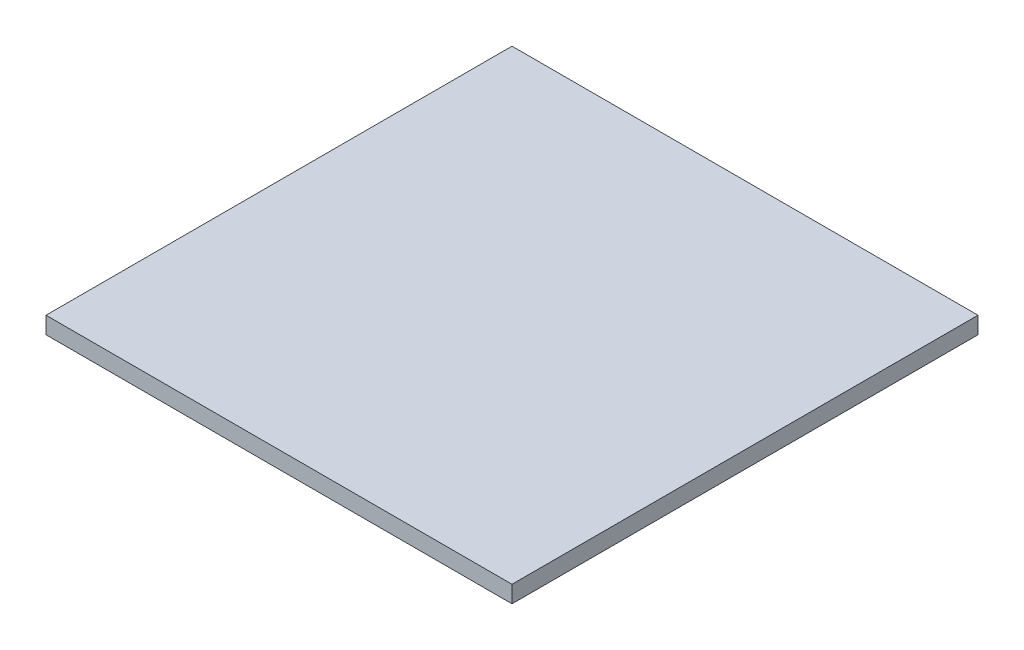
SolidWorks part; units mm, degrees
ref_plane "Front Plane" through (0, 0, 0) normal (0, 0, 1) x (1, 0, 0)
ref_plane "Top Plane" through (0, 0, 0) normal (0, 1, 0) x (1, 0, 0)
ref_plane "Right Plane" through (0, 0, 0) normal (1, 0, 0) x (0, 0, -1)
sketch "Sketch1" plane through (0, 0, 0) normal (0, 1, 0) x (1, 0, 0)
  line L1 (-275, 275) -> (275, 275)
  line L2 (-275, 275) -> (-275, -275)
  line L3 (-275, -275) -> (275, -275)
  line L4 (275, 275) -> (275, -275)
  line L5 (-275, 275) -> (275, -275) construction
  line L6 (-275, -275) -> (275, 275) construction
  point P0 (0, 0)
  dimension "D1" = 550
extrude "Boss-Extrude1" add sketch "Sketch1" along normal blind 20
